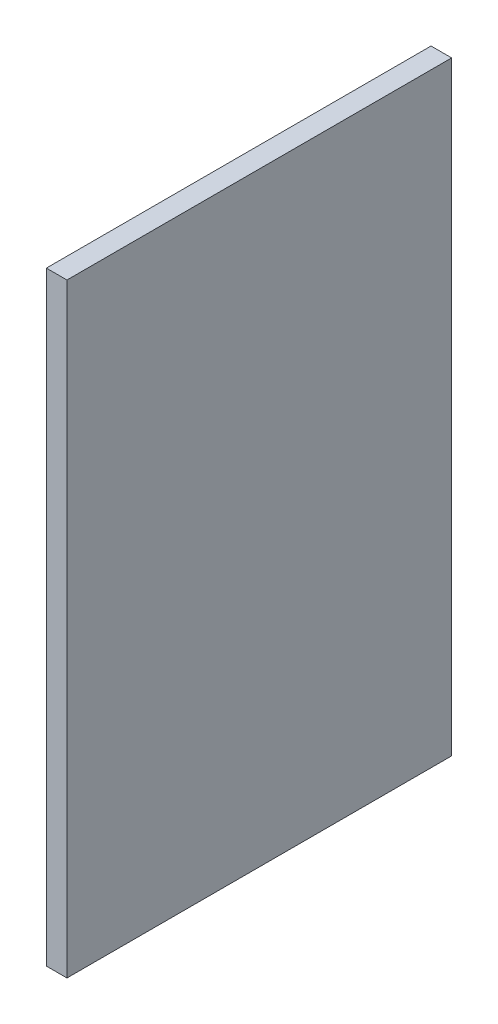
SolidWorks part; units mm, degrees
ref_plane "Front Plane" through (0, 0, 0) normal (0, 0, 1) x (1, 0, 0)
ref_plane "Top Plane" through (0, 0, 0) normal (0, 1, 0) x (1, 0, 0)
ref_plane "Right Plane" through (0, 0, 0) normal (1, 0, 0) x (0, 0, -1)
sketch "Sketch1" plane through (0, 0, 0) normal (1, 0, 0) x (0, 0, -1)
  line L1 (177.8, 279.4) -> (-177.8, 279.4)
  line L2 (177.8, 279.4) -> (177.8, -279.4)
  line L3 (177.8, -279.4) -> (-177.8, -279.4)
  line L4 (-177.8, 279.4) -> (-177.8, -279.4)
  line L5 (177.8, 279.4) -> (-177.8, -279.4) construction
  line L6 (177.8, -279.4) -> (-177.8, 279.4) construction
  point P0 (0, 0)
  dimension "D1" = 558.8
  dimension "D2" = 355.6
extrude "Boss-Extrude1" add sketch "Sketch1" along normal blind 19.05
